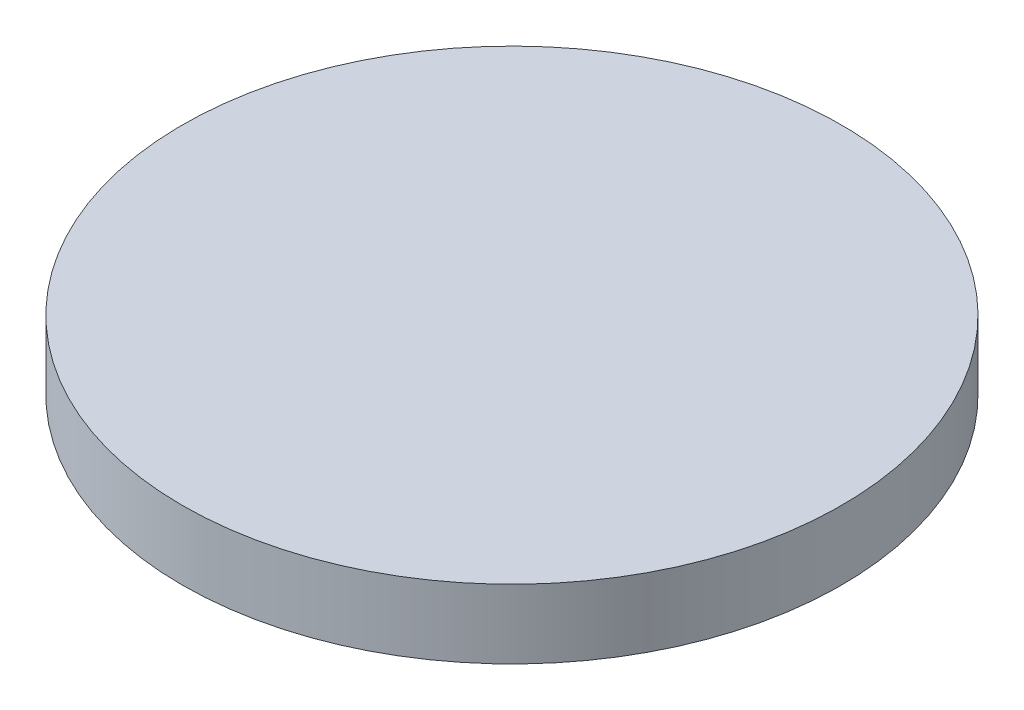
SolidWorks part; units mm, degrees
ref_plane "Front Plane" through (0, 0, 0) normal (0, 0, 1) x (1, 0, 0)
ref_plane "Top Plane" through (0, 0, 0) normal (0, 1, 0) x (1, 0, 0)
ref_plane "Right Plane" through (0, 0, 0) normal (1, 0, 0) x (0, 0, -1)
sketch "Sketch1" plane through (0, 0, 0) normal (0, 1, 0) x (1, 0, 0)
  circle A0 centre (0, 0) radius 10.025
  dimension "D1" = 20.05
extrude "Boss-Extrude1" add sketch "Sketch1" along normal blind 2.1
sketch "Sketch2" plane through (0, 0, 0) normal (0, -1, 0) x (-1, 0, 0)
  circle A0 centre (0, 0) radius 4.3
  dimension "D1" = 8.6
extrude "Boss-Extrude2" add sketch "Sketch2" along normal blind 2.1
